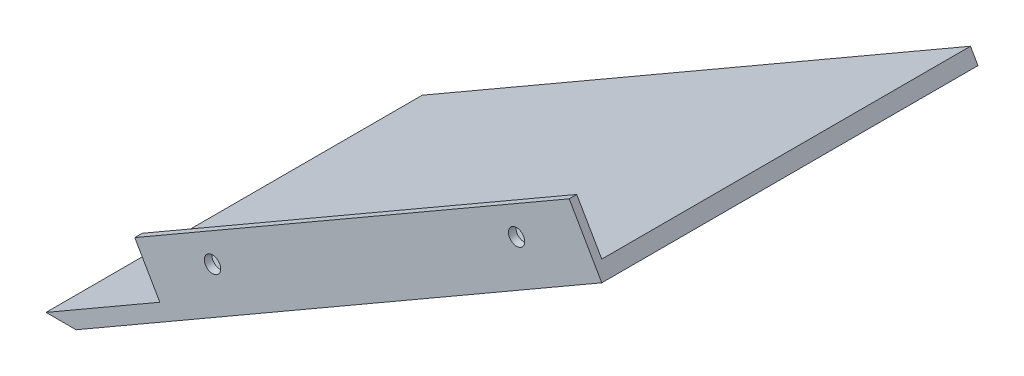
SolidWorks part; units mm, degrees
ref_plane "Front Plane" through (0, 0, 0) normal (0, 0, 1) x (1, 0, 0)
ref_plane "Top Plane" through (0, 0, 0) normal (0, 1, 0) x (1, 0, 0)
ref_plane "Right Plane" through (0, 0, 0) normal (1, 0, 0) x (0, 0, -1)
sketch "Sketch1" plane through (0, 0, 0) normal (0, 0, 1) x (1, 0, 0)
  line L0 (0, 0) -> (6, 0)
  line L1 (6, 0) -> (110.7977, 60.505)
  line L2 (6, 0) -> (50006, 0) construction
  line L3 (110.7977, 60.505) -> (109.2977, 63.1031)
  line L4 (0, 0) -> (109.2977, 63.1031)
  dimension "D1" = 6
  dimension "D2" = 121.01
  dimension "D3" = 30
  dimension "D4" = 3
extrude "Boss-Extrude1" add sketch "Sketch1" along normal blind 75
sketch "Sketch2" plane through (0, 0, 0) normal (-0.5, 0.866, 0) x (0.866, 0.5, 0)
  line L1 (126.2062, -75) -> (26.2062, -75)
  line L2 (126.2062, -75) -> (126.2062, -73.5)
  line L3 (126.2062, -73.5) -> (26.2062, -73.5)
  line L4 (26.2062, -75) -> (26.2062, -73.5)
  dimension "D1" = 100
  dimension "D2" = 1.5
extrude "Boss-Extrude2" add sketch "Sketch2" along normal blind 10
sketch "Sketch3" plane through (0, 0, 75) normal (0, 0, 1) x (1, 0, 0)
  line L1 (17.6952, 21.7633) -> (22.6952, 13.1031) construction
  line L2 (110.7977, 60.505) -> (104.2977, 71.7633) construction
  line L8 (17.6952, 21.7633) -> (104.2977, 71.7633) construction
  circle A0 centre (33.1981, 24.9114) radius 1.625
  circle A1 centre (93.8074, 59.9332) radius 1.625
  point P7 (0, 0)
  point P8 (0, 0)
  point P16 (95.642, 56.7556)
  dimension "D2" = 15
  dimension "D3" = 15
  dimension "D4" = 3.25
  dimension "D5" = 3.25
  dimension "D6" = 5
  dimension "D7" = 5.0251
extrude "Cut-Extrude1" cut sketch "Sketch3" against normal through all
